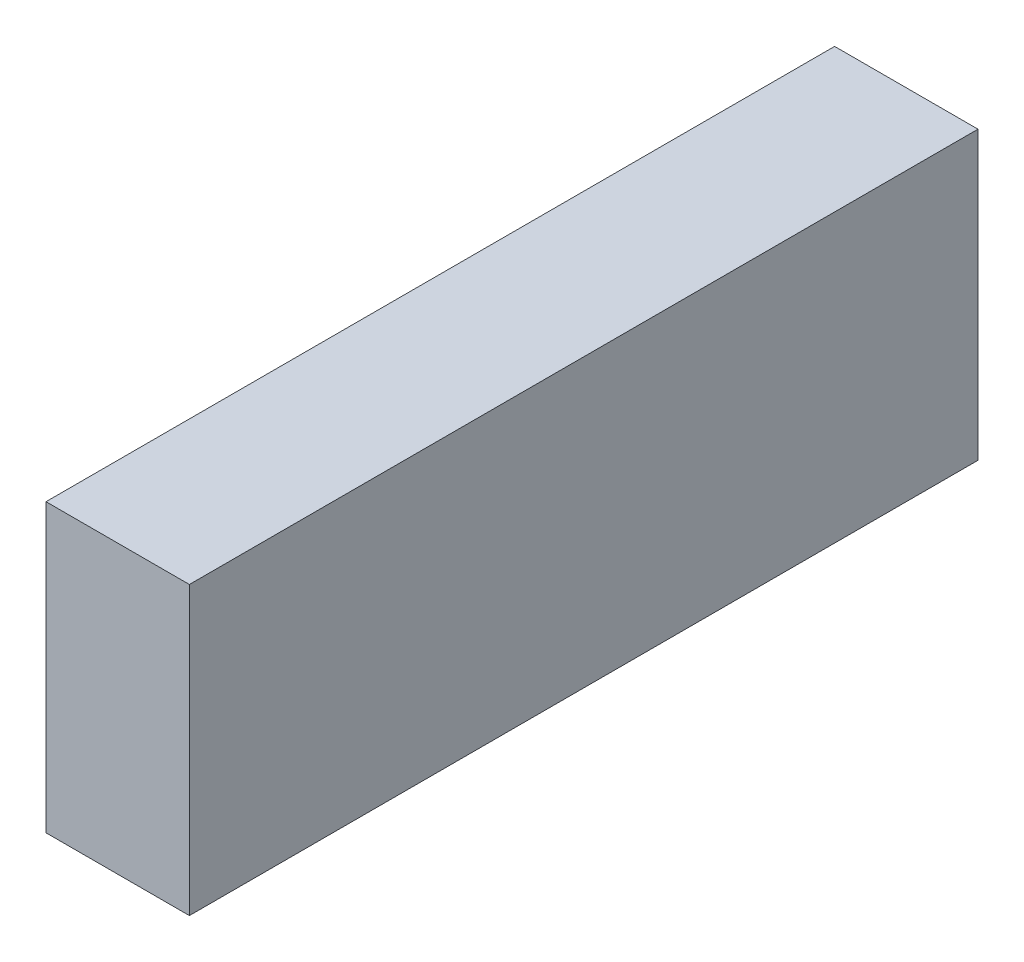
SolidWorks part; units mm, degrees
ref_plane "Front Plane" through (0, 0, 0) normal (0, 0, 1) x (1, 0, 0)
ref_plane "Top Plane" through (0, 0, 0) normal (0, 1, 0) x (1, 0, 0)
ref_plane "Right Plane" through (0, 0, 0) normal (1, 0, 0) x (0, 0, -1)
sketch "Sketch1" plane through (0, 0, 0) normal (0, 1, 0) x (1, 0, 0)
  line L1 (-12.7, -69.85) -> (12.7, -69.85)
  line L2 (-12.7, -69.85) -> (-12.7, 69.85)
  line L3 (-12.7, 69.85) -> (12.7, 69.85)
  line L4 (12.7, -69.85) -> (12.7, 69.85)
  line L5 (-12.7, -69.85) -> (12.7, 69.85) construction
  line L6 (-12.7, 69.85) -> (12.7, -69.85) construction
  point P0 (0, 0)
  dimension "D1" = 25.4
  dimension "D2" = 139.7
extrude "Boss-Extrude1" add sketch "Sketch1" along normal blind 6.35
sketch "Sketch3" plane through (0, 6.35, 0) normal (0, 1, 0) x (1, 0, 0)
  line L0 (12.7, -69.85) -> (12.7, 69.85) construction
  line L1 (-12.7, 69.85) -> (12.7, 69.85)
  line L2 (-12.7, 69.85) -> (-12.7, 63.5)
  line L3 (-12.7, 63.5) -> (12.7, 63.5)
  line L4 (12.7, 69.85) -> (12.7, 63.5)
  line L6 (-12.7, -69.85) -> (12.7, -69.85)
  line L7 (-12.7, -69.85) -> (-12.7, -63.5)
  line L8 (-12.7, -63.5) -> (12.7, -63.5)
  line L9 (12.7, -69.85) -> (12.7, -63.5)
  dimension "D1" = 6.35
extrude "Boss-Extrude2" add sketch "Sketch3" along normal blind 38.1
sketch "Sketch6" plane through (0, 6.35, 0) normal (0, 1, 0) x (1, 0, 0)
  line L0 (12.7, -63.5) -> (12.7, 63.5) construction
  line L1 (12.7, 50.8) -> (19.05, 50.8)
  line L2 (12.7, 50.8) -> (12.7, 38.1)
  line L3 (12.7, 38.1) -> (19.05, 38.1)
  line L5 (12.7, 69.85) -> (-12.7, 69.85) construction
  line L6 (19.05, 57.15) -> (25.4, 57.15)
  line L7 (19.05, 57.15) -> (19.05, 50.8)
  line L8 (19.05, 31.75) -> (25.4, 31.75)
  line L9 (25.4, 57.15) -> (25.4, 31.75)
  line L10 (19.05, 38.1) -> (19.05, 31.75)
  point P10 (25.4, 44.45)
  point P11 (12.7, 44.45)
  dimension "D1" = 6.35
  dimension "D2" = 12.7
  dimension "D3" = 25.4
  dimension "D4" = 6.35
  dimension "D5" = 25.4
extrude "Boss-Extrude3" add sketch "Sketch6" against normal up to surface (6.35 mm away) up to face at (0, 0, 0)
sketch "Sketch7" plane through (0, 6.35, 0) normal (0, 1, 0) x (1, 0, 0)
  line L0 (-12.7, 63.5) -> (-12.7, -63.5) construction
  line L1 (-12.7, 50.8) -> (-6.35, 50.8)
  line L2 (-12.7, 50.8) -> (-12.7, 38.1)
  line L3 (-12.7, 38.1) -> (-6.35, 38.1)
  line L5 (-6.35, 38.1) -> (-6.35, 31.75)
  line L6 (0, 57.15) -> (-6.35, 57.15)
  line L7 (0, 57.15) -> (0, 31.75)
  line L8 (0, 31.75) -> (-6.35, 31.75)
  line L9 (-6.35, 57.15) -> (-6.35, 50.8)
  line L10 (19.05, 50.8) -> (12.7, 50.8) construction
  line L11 (25.4, 57.15) -> (19.05, 57.15) construction
  line L12 (19.05, 57.15) -> (19.05, 50.8) construction
  line L13 (25.4, 31.75) -> (25.4, 57.15) construction
extrude "Cut-Extrude2" cut sketch "Sketch7" against normal through all
mirror "Mirror1" about plane through (0, 0, 0) normal (0, 0, 1) of "Boss-Extrude3", "Cut-Extrude2"
sketch "Sketch8" plane through (0, 6.35, 0) normal (0, 1, 0) x (1, 0, 0)
  line L0 (-12.7, -69.85) -> (12.7, -69.85) construction
  line L1 (12.7, 69.85) -> (25.4, 69.85)
  line L2 (12.7, 69.85) -> (12.7, -69.85)
  line L3 (12.7, -69.85) -> (25.4, -69.85)
  line L4 (25.4, 69.85) -> (25.4, -69.85)
  line L5 (25.4, 31.75) -> (25.4, 57.15) construction
extrude "Cut-Extrude3" cut sketch "Sketch8" against normal through all
sketch "Sketch9" plane through (0, 6.35, 0) normal (0, 1, 0) x (1, 0, 0)
  line L0 (12.7, -63.5) -> (-12.7, -63.5) construction
  line L1 (12.7, 63.5) -> (6.35, 63.5)
  line L2 (12.7, 63.5) -> (12.7, -63.5)
  line L3 (12.7, -63.5) -> (6.35, -63.5)
  line L4 (6.35, 63.5) -> (6.35, -63.5)
  line L5 (-12.7, -63.5) -> (-12.7, -69.85) construction
extrude "Boss-Extrude4" add sketch "Sketch9" along normal up to surface (38.1 mm away) up to face at (0, 44.45, 66.675)
sketch "Sketch10" plane through (0, 44.45, 0) normal (0, 1, 0) x (1, 0, 0)
  line L1 (-12.7, 69.85) -> (12.7, 69.85)
  line L2 (-12.7, 69.85) -> (-12.7, -69.85)
  line L3 (-12.7, -69.85) -> (12.7, -69.85)
  line L4 (12.7, 69.85) -> (12.7, -69.85)
extrude "Boss-Extrude5" add sketch "Sketch10" along normal blind 6.35
